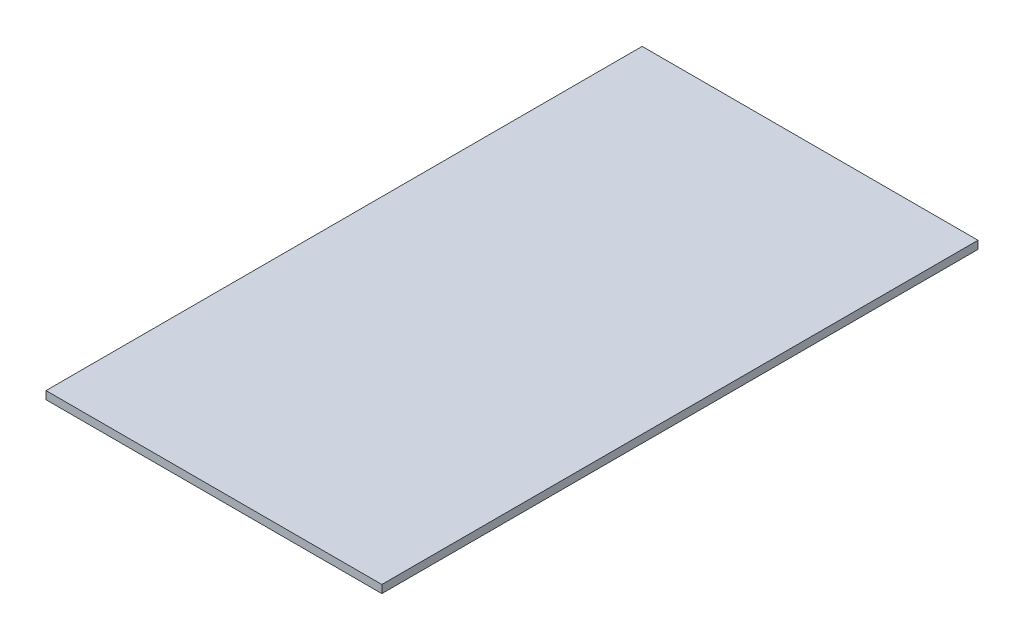
SolidWorks part; units mm, degrees
ref_plane "Front Plane" through (0, 0, 0) normal (0, 0, 1) x (1, 0, 0)
ref_plane "Top Plane" through (0, 0, 0) normal (0, 1, 0) x (1, 0, 0)
ref_plane "Right Plane" through (0, 0, 0) normal (1, 0, 0) x (0, 0, -1)
sketch "Sketch1" plane through (0, 0, 0) normal (0, 1, 0) x (1, 0, 0)
  line L1 (0, 0) -> (338, 0)
  line L2 (0, 0) -> (0, 600)
  line L3 (0, 600) -> (338, 600)
  line L4 (338, 0) -> (338, 600)
  dimension "D1" = 600
  dimension "D2" = 338
extrude "Boss-Extrude1" add sketch "Sketch1" along normal blind 8
